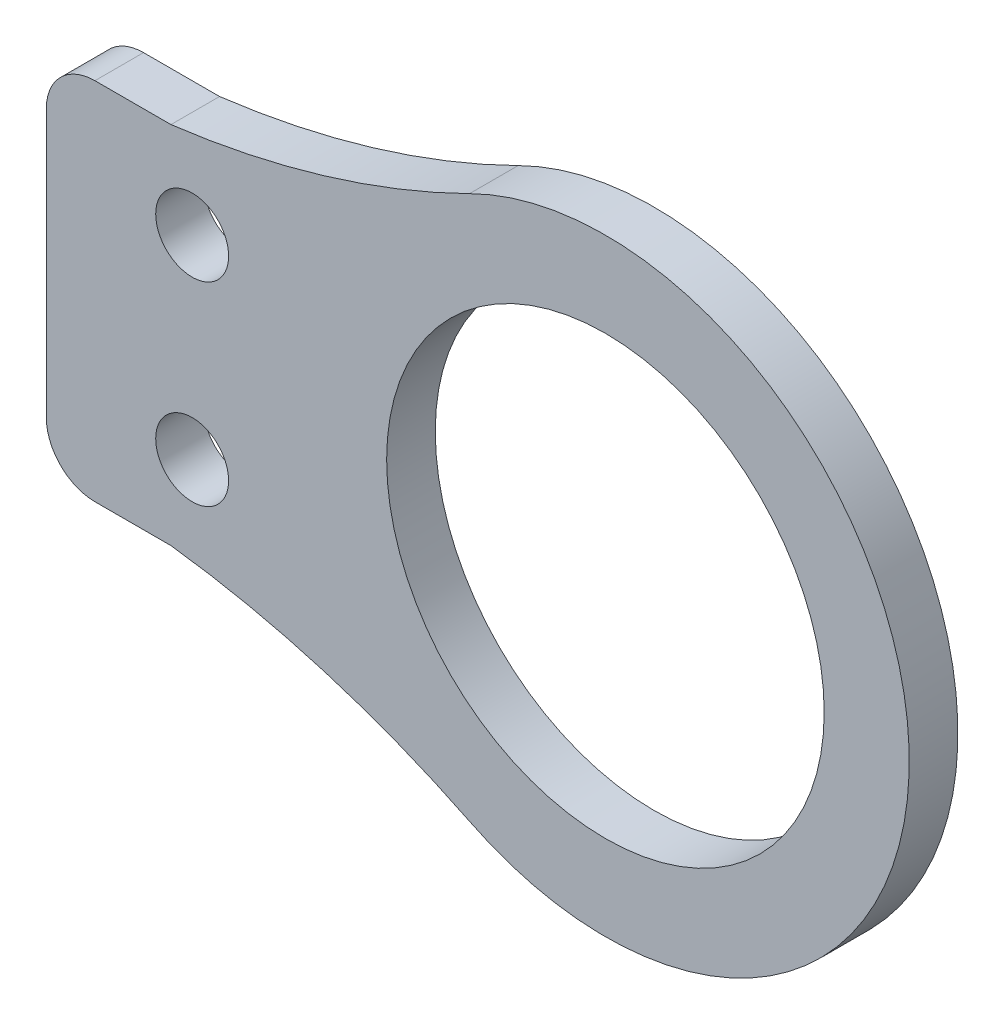
SolidWorks part; units mm, degrees
ref_plane "前视基准面" through (0, 0, 0) normal (0, 0, 1) x (1, 0, 0)
ref_plane "上视基准面" through (0, 0, 0) normal (0, 1, 0) x (1, 0, 0)
ref_plane "右视基准面" through (0, 0, 0) normal (1, 0, 0) x (0, 0, -1)
sketch "草图1" plane through (0, 0, 0) normal (0, 0, 1) x (1, 0, 0)
  circle A0 centre (0, 0) radius 9
  circle A1 centre (0, 0) radius 12.5
  dimension "D1" = 18
  dimension "D2" = 25
extrude "凸台-拉伸1" add sketch "草图1" along normal blind 1
sketch "草图2" plane through (0, 0, 0) normal (0, 0, -1) x (-1, 0, 0)
  line L0 (0, 0) -> (17, 0) construction
  line L1 (17, 0) -> (17, 4) construction
  line L2 (17, 0) -> (17, -4) construction
  line L6 (17.8724, 7.5) -> (23, 7.5)
  line L7 (23, -7.5) -> (23, 7.5)
  line L8 (17, 0) -> (23, 0) construction
  line L9 (17.8724, -7.5) -> (23, -7.5)
  circle A0 centre (0, 0) radius 12.5 construction
  arc A1 (5.5908, -11.18) -> (5.5908, 11.18) centre (0, 0) ccw
  arc A2 (5.5908, 11.18) -> (17.8724, 7.5) centre (22.6143, 45.6597) ccw
  circle A4 centre (17, 4) radius 1.5
  circle A5 centre (17, -4) radius 1.5
  arc A6 (5.5908, -11.18) -> (17.8724, -7.5) centre (22.6143, -45.6597) cw
  dimension "D1" = 6
extrude "凸台-拉伸2" add sketch "草图2" against normal blind 1
sketch "草图3" plane through (0, 0, 0) normal (0, 0, -1) x (-1, 0, 0)
  line L3 (17.8724, -7.5) -> (23, -7.5)
  line L4 (23, -7.5) -> (23, 7.5)
  line L5 (23, 7.5) -> (17.8724, 7.5)
  line L7 (23, -7.5) -> (23, 7.5)
  line L8 (23, 7.5) -> (17.8724, 7.5)
  line L9 (17.8724, -7.5) -> (23, -7.5)
  circle A0 centre (17, -4) radius 1.5 construction
  circle A1 centre (17, 4) radius 1.5 construction
  circle A2 centre (0, 0) radius 9 construction
  circle A3 centre (17, -4) radius 1.5
  circle A4 centre (17, 4) radius 1.5
  arc A5 (17.8724, -7.5) -> (5.5908, -11.18) centre (22.6143, -45.6597) ccw
  arc A7 (5.5908, 11.18) -> (17.8724, 7.5) centre (22.6143, 45.6597) ccw
  arc A8 (5.5908, 11.18) -> (5.5908, -11.18) centre (0, 0) ccw
  arc A9 (17.8724, -7.5) -> (5.5908, -11.18) centre (22.6143, -45.6597) ccw
  arc A12 (5.5908, 11.18) -> (17.8724, 7.5) centre (22.6143, 45.6597) ccw
  arc A13 (5.5908, 11.18) -> (5.5908, -11.18) centre (0, 0) ccw
  circle A15 centre (0, 0) radius 9
  dimension "D1" = 0
extrude "凸台-拉伸3" add sketch "草图3" along normal blind 1
fillet "圆角2" radius 2 2 edges at (-23, -7.5, 0) (-23, 7.5, 0)
